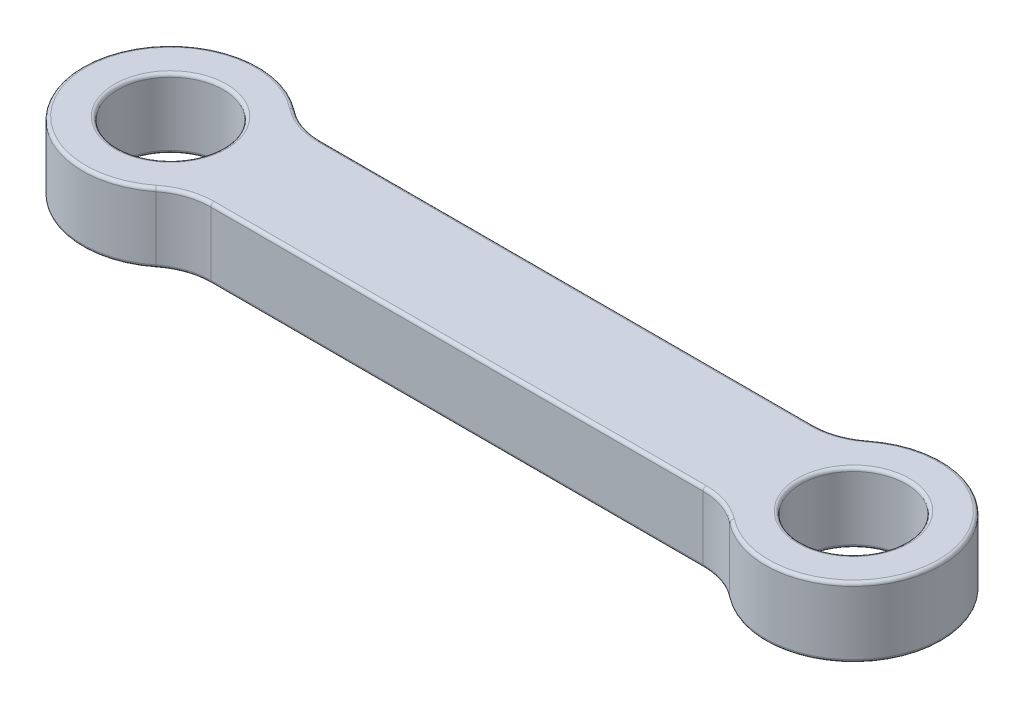
SolidWorks part; units mm, degrees
ref_plane "Front Plane" through (0, 0, 0) normal (0, 0, 1) x (1, 0, 0)
ref_plane "Top Plane" through (0, 0, 0) normal (0, 1, 0) x (1, 0, 0)
ref_plane "Right Plane" through (0, 0, 0) normal (1, 0, 0) x (0, 0, -1)
sketch "Sketch1" plane through (0, 0, 0) normal (0, 1, 0) x (1, 0, 0)
  line L1 (-12.3775, 2.5) -> (12.3775, 2.5)
  line L2 (-12.3775, 2.5) -> (-12.3775, -2.5) construction
  line L3 (-12.3775, -2.5) -> (12.3775, -2.5)
  line L4 (12.3775, 2.5) -> (12.3775, -2.5) construction
  line L5 (-12.3775, 2.5) -> (12.3775, -2.5) construction
  line L6 (-12.3775, -2.5) -> (12.3775, 2.5) construction
  circle A0 centre (15.5, 0) radius 2.395
  circle A1 centre (-15.5, 0) radius 2.395
  circle A2 centre (-15.5, 0) radius 4
  circle A3 centre (15.5, 0) radius 4
  point P0 (0, 0)
  point P12 (-12.3465, 2.3153)
  point P13 (-12.2847, -2.1301)
  point P14 (0, 0)
  point P15 (0, 0)
  dimension "D2" = 4.79
  dimension "D3" = 8
  dimension "D1" = 31
  dimension "D4" = 5
extrude "Boss-Extrude1" add sketch "Sketch1" along normal blind 3.175 contours A2 A1 | A3 L1 A2 L3 | A3 A0
fillet "Fillet1" radius 3 4 edges at (-12.3775, 1.5875, -2.5) (12.3775, 1.5875, -2.5) (12.3775, 1.5875, 2.5) (-12.3775, 1.5875, 2.5)
fillet "Fillet2" radius 0.15 20 edges at (15.5, 0, 2.395) (-12.1519, 0, 2.6653) (0, 0, 2.5) (12.1519, 0, 2.6653) (19.5, 0, 0) (12.1519, 0, -2.6653) (0, 0, -2.5) (-12.1519, 0, -2.6653) (-19.5, 0, 0) (-15.5, 0, 2.395) (15.5, 3.175, 2.395) (12.1519, 3.175, -2.6653) (19.5, 3.175, 0) (12.1519, 3.175, 2.6653) (0, 3.175, 2.5) (-12.1519, 3.175, 2.6653) (-19.5, 3.175, 0) (-12.1519, 3.175, -2.6653) (0, 3.175, -2.5) (-15.5, 3.175, 2.395)
